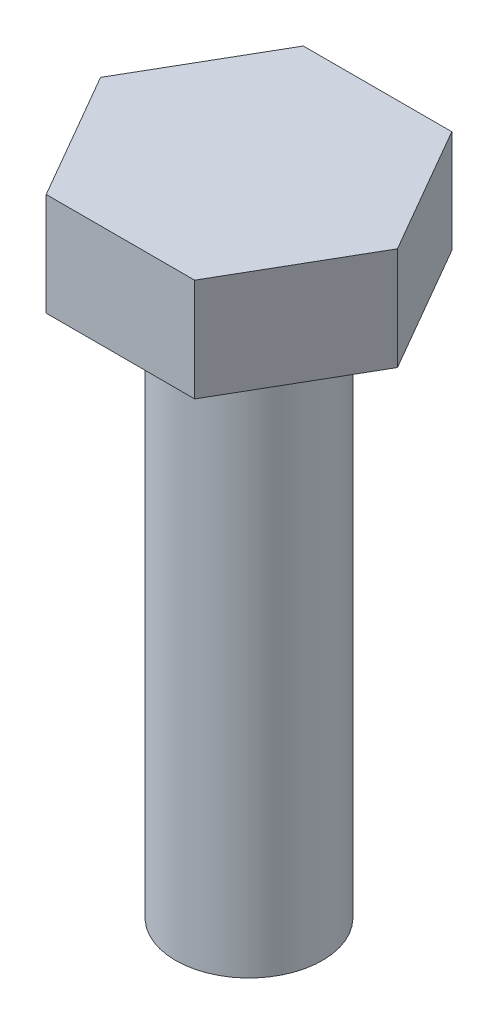
SolidWorks part; units mm, degrees
ref_plane "前视基准面" through (0, 0, 0) normal (0, 0, 1) x (1, 0, 0)
ref_plane "上视基准面" through (0, 0, 0) normal (0, 1, 0) x (1, 0, 0)
ref_plane "右视基准面" through (0, 0, 0) normal (1, 0, 0) x (0, 0, -1)
sketch "草图1" plane through (0, 0, 0) normal (0, 1, 0) x (1, 0, 0)
  circle A0 centre (0, 0) radius 2
  dimension "D1" = 4
extrude "凸台-拉伸1" add sketch "草图1" along normal blind 15
sketch "草图2" plane through (0, 15, 0) normal (0, 1, 0) x (1, 0, 0)
  line L1 (4.0415, 0) -> (2.0207, 3.5)
  line L2 (2.0207, 3.5) -> (-2.0207, 3.5)
  line L3 (-2.0207, 3.5) -> (-4.0415, 0)
  line L4 (-4.0415, 0) -> (-2.0207, -3.5)
  line L5 (-2.0207, -3.5) -> (2.0207, -3.5)
  line L6 (2.0207, -3.5) -> (4.0415, 0)
  circle A0 centre (0, 0) radius 3.5 construction
  dimension "D1" = 7
extrude "凸台-拉伸2" add sketch "草图2" along normal blind 2.8
